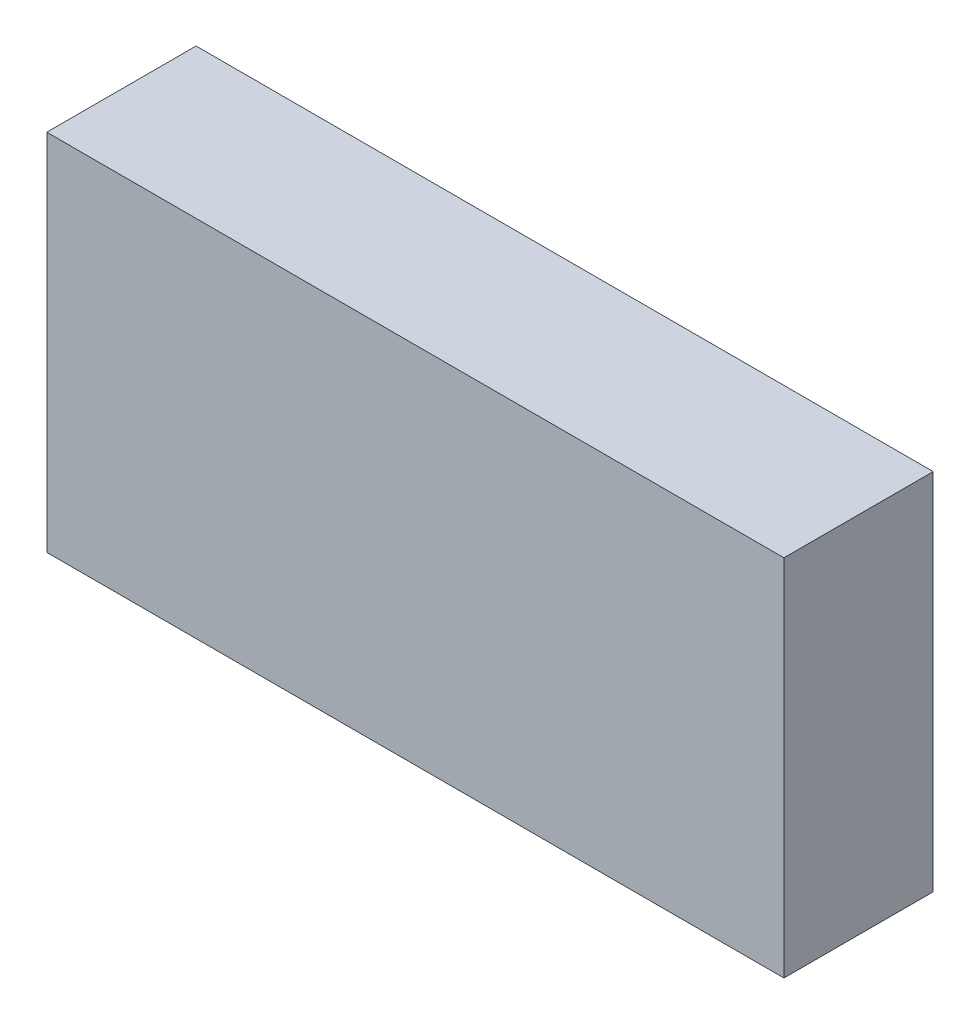
SolidWorks part; units mm, degrees
ref_plane "Спереди" through (0, 0, 0) normal (0, 0, 1) x (1, 0, 0)
ref_plane "Сверху" through (0, 0, 0) normal (0, 1, 0) x (1, 0, 0)
ref_plane "Справа" through (0, 0, 0) normal (1, 0, 0) x (0, 0, -1)
sketch "Эскиз1" plane through (0, 0, 0) normal (0, 0, 1) x (1, 0, 0)
  line L1 (-7.9, -3.9) -> (7.9, -3.9)
  line L2 (-7.9, -3.9) -> (-7.9, 3.9)
  line L3 (-7.9, 3.9) -> (7.9, 3.9)
  line L4 (7.9, -3.9) -> (7.9, 3.9)
  line L5 (-7.9, -3.9) -> (7.9, 3.9) construction
  line L6 (-7.9, 3.9) -> (7.9, -3.9) construction
  point P0 (0, 0)
  dimension "D1" = 15.8
  dimension "D2" = 7.8
extrude "Бобышка-Вытянуть1" add sketch "Эскиз1" along normal blind 3.2
sketch "Эскиз2" plane through (0, 0, 0) normal (0, 0, -1) x (-1, 0, 0)
  circle A0 centre (-4, 0) radius 2.5
  circle A1 centre (4, 0) radius 2.5
  dimension "D1" = 4
  dimension "D2" = 4
extrude "Вырез-Вытянуть1" cut sketch "Эскиз2" against normal blind 1.8
